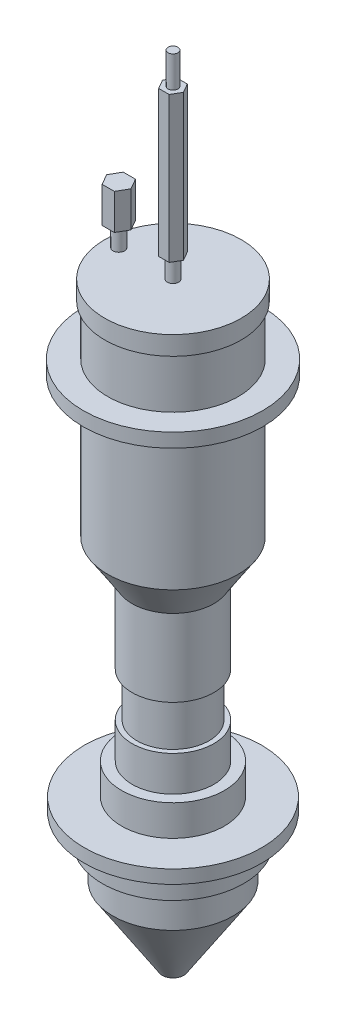
SolidWorks part; units mm, degrees
ref_plane "前视基准面" through (0, 0, 0) normal (0, 0, 1) x (1, 0, 0)
ref_plane "上视基准面" through (0, 0, 0) normal (0, 1, 0) x (1, 0, 0)
ref_plane "右视基准面" through (0, 0, 0) normal (1, 0, 0) x (0, 0, -1)
sketch "草图1" plane through (0, 0, 0) normal (0, 0, 1) x (1, 0, 0)
  line L0 (0, 0) -> (0, 690.98) construction
  line L1 (0, 0) -> (7.5, 0)
  line L2 (7.5, 0) -> (42.09, 53.35)
  line L3 (42.09, 53.35) -> (42.09, 76.73)
  line L4 (42.09, 76.73) -> (49.525, 76.73)
  line L5 (49.525, 76.73) -> (49.525, 95.5)
  line L6 (49.525, 95.5) -> (62.215, 95.5)
  line L7 (62.215, 95.5) -> (62.215, 104.91)
  line L8 (62.215, 104.91) -> (36.02, 104.91)
  line L9 (36.02, 104.91) -> (36.02, 126.55)
  line L10 (36.02, 126.55) -> (28.645, 126.55)
  line L11 (28.645, 126.55) -> (28.645, 151.31)
  line L12 (28.645, 151.31) -> (25.25, 151.31)
  line L13 (25.25, 151.31) -> (25.25, 182.28)
  line L14 (25.25, 182.28) -> (28.645, 182.28)
  line L15 (28.645, 182.28) -> (28.645, 236.27)
  line L17 (45.765, 262.67) -> (45.765, 360.73)
  line L18 (45.765, 360.73) -> (62.835, 360.73)
  line L19 (62.835, 360.73) -> (62.835, 370.54)
  line L20 (62.835, 370.54) -> (45.765, 370.54)
  line L21 (45.765, 370.54) -> (45.765, 405.93)
  line L22 (45.765, 405.93) -> (47.82, 405.93)
  line L48 (47.82, 419.14) -> (0, 419.14)
  line L49 (0, 419.14) -> (0, 0)
  line L50 (28.645, 236.27) -> (45.765, 262.67)
  line L51 (47.82, 405.93) -> (47.82, 419.14)
  dimension "D1" = 15
  dimension "D2" = 53.35
  dimension "D3" = 84.18
  dimension "D4" = 99.05
  dimension "D5" = 23.38
  dimension "D6" = 18.77
  dimension "D7" = 124.43
  dimension "D8" = 9.41
  dimension "D9" = 72.04
  dimension "D10" = 21.64
  dimension "D11" = 57.29
  dimension "D12" = 24.76
  dimension "D13" = 50.5
  dimension "D14" = 30.97
  dimension "D16" = 57.29
  dimension "D20" = 9.81
  dimension "D15" = 53.99
  dimension "D18" = 26.4
  dimension "D19" = 98.06
  dimension "D17" = 91.53
  dimension "D21" = 125.67
  dimension "D22" = 91.53
  dimension "D23" = 95.64
  dimension "D24" = 13.21
  dimension "D25" = 35.39
revolve "旋转1" add sketch "草图1" angle 360 about L0
sketch "草图2" plane through (0, 419.14, 0) normal (0, 1, 0) x (1, 0, 0)
  circle A0 centre (0, 0) radius 4
  circle A1 centre (-38, 0) radius 4
  dimension "D1" = 8
  dimension "D2" = 38
extrude "凸台-拉伸1" add sketch "草图2" along normal blind 15
sketch "草图3" plane through (0, 434.14, 0) normal (0, 1, 0) x (1, 0, 0)
  line L1 (3.6748, -6.365) -> (7.3497, 0)
  line L2 (7.3497, 0) -> (3.6748, 6.365)
  line L3 (3.6748, 6.365) -> (-3.6748, 6.365)
  line L4 (-3.6748, 6.365) -> (-7.3497, 0)
  line L5 (-7.3497, 0) -> (-3.6748, -6.365)
  line L6 (-3.6748, -6.365) -> (3.6748, -6.365)
  circle A0 centre (0, 0) radius 6.365 construction
  dimension "D1" = 12.73
extrude "凸台-拉伸2" add sketch "草图3" along normal blind 102
sketch "草图4" plane through (0, 536.14, 0) normal (0, 1, 0) x (1, 0, 0)
  circle A0 centre (0, 0) radius 3.42
  dimension "D1" = 6.84
extrude "凸台-拉伸3" add sketch "草图4" along normal blind 22
sketch "草图5" plane through (0, 434.14, 0) normal (0, 1, 0) x (1, 0, 0)
  line L1 (-29.4494, 0) -> (-33.7247, 7.405)
  line L2 (-33.7247, 7.405) -> (-42.2753, 7.405)
  line L3 (-42.2753, 7.405) -> (-46.5506, 0)
  line L4 (-46.5506, 0) -> (-42.2753, -7.405)
  line L5 (-42.2753, -7.405) -> (-33.7247, -7.405)
  line L6 (-33.7247, -7.405) -> (-29.4494, 0)
  circle A0 centre (-38, 0) radius 7.405 construction
  dimension "D1" = 14.81
extrude "凸台-拉伸4" add sketch "草图5" along normal blind 25
equation "\"D22@草图1\"=\"D17@草图1\""
